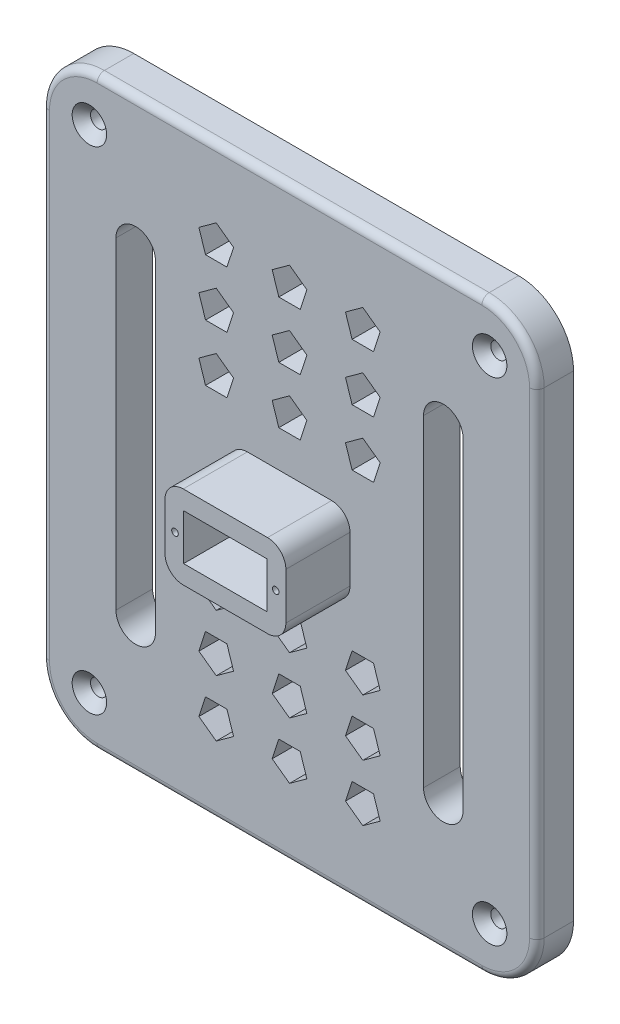
SolidWorks part; units mm, degrees
ref_plane "Front Plane" through (0, 0, 0) normal (1, 0, 0) x (0, 1, 0)
ref_plane "Top Plane" through (0, 0, 0) normal (0, 0, 1) x (0, 1, 0)
ref_plane "Right Plane" through (0, 0, 0) normal (0, 1, 0) x (-1, 0, 0)
sketch "Sketch1" plane through (0, 0, 0) normal (0, 0, 1) x (0, 1, 0)
  line L1 (-60, 62.5) -> (60, 62.5)
  line L2 (-75, 47.5) -> (-75, -47.5)
  line L3 (-60, -62.5) -> (60, -62.5)
  line L4 (75, 47.5) -> (75, -47.5)
  line L5 (-75, 62.5) -> (75, -62.5) construction
  line L6 (-75, -62.5) -> (75, 62.5) construction
  arc A0 (-75, -47.5) -> (-60, -62.5) centre (-60, -47.5) ccw
  arc A1 (60, -62.5) -> (75, -47.5) centre (60, -47.5) ccw
  arc A2 (60, 62.5) -> (75, 47.5) centre (60, 47.5) cw
  arc A3 (-60, 62.5) -> (-75, 47.5) centre (-60, 47.5) ccw
  point P0 (0, 0)
  dimension "D3" = 15
  dimension "D1" = 150
  dimension "D2" = 125
extrude "Boss-Extrude1" add sketch "Sketch1" along normal blind 10
hole_wizard "CSK for M4 Countersunk Flat Head Screw1" positions "Sketch2" profile "Sketch3" countersink size "M4" standard "ISO"
sketch "Sketch2" plane through (0, 0, 10) normal (0, 0, 1) x (0, -1, 0)
  line L0 (-75, 47.5) -> (-75, -47.5) construction
  line L1 (0, 0) -> (0, 48.1391) construction
  line L3 (0, 0) -> (-58.4217, 0) construction
  line L4 (60, 62.5) -> (-60, 62.5) construction
  point P0 (-67.11, 54.61)
  point P15 (67.11, 54.61)
  point P17 (67.11, -54.61)
  point P18 (-67.11, -54.61)
  dimension "D1" = 7.89
  dimension "D2" = 7.89
sketch "Sketch3" plane through (54.61, 67.11, 10) normal (1, 0, 0) x (0, -1, 0)
  line L0 (0, 0) -> (0, 11.3219)
  line L1 (0, 11.3219) -> (2.2, 10)
  line L2 (2.2, 10) -> (2.2, 2.5)
  line L3 (2.2, 2.5) -> (4.7, 0)
  line L5 (4.7, 0) -> (0, 0)
  line L6 (-2.2, 2.5) -> (-4.7, 0) construction
  line L10 (0, 11.3219) -> (-2.2, 10) construction
  line L11 (0, -6.35) -> (0, 107.95) construction
  dimension "Hole Dia." = 4.4
  dimension "Hole Depth" = 10
  dimension "Near C'Sink Dia." = 9.4
  dimension "Near C'Sink Angle" = 90
  dimension "Drill Angle" = 118
sketch "Sketch4" plane through (0, 0, 10) normal (0, 0, 1) x (1, 0, 0)
  line L1 (-11.4, 6.25) -> (11.4, 6.25)
  line L2 (-11.4, 6.25) -> (-11.4, -6.25)
  line L3 (-11.4, -6.25) -> (11.4, -6.25)
  line L4 (11.4, 6.25) -> (11.4, -6.25)
  line L5 (-11.4, 6.25) -> (11.4, -6.25) construction
  line L6 (-11.4, -6.25) -> (11.4, 6.25) construction
  point P0 (0, 0)
  dimension "D1" = 22.8
  dimension "D2" = 12.5
extrude "Extrude-Thin1" add sketch "Sketch4" along normal blind 17.5 thin thin type one direction wall 5.1
fillet "Fillet1" radius 5 4 edges at (16.5, -11.35, 18.75) (16.5, 11.35, 18.75) (-16.5, 11.35, 18.75) (-16.5, -11.35, 18.75)
sketch "Sketch5" plane through (0, 0, 27.5) normal (0, 0, 1) x (1, 0, 0)
  line L0 (0, 0) -> (0, 14.7262) construction
  point P3 (13.75, 0)
  point P4 (-13.75, 0)
  dimension "D1" = 13.75
hole_wizard "Ø1.5mm Dowel Hole1" positions "Sketch6" profile "Sketch7" hole size "Ø1.5" standard "ISO"
sketch "Sketch6" plane through (0, 0, 27.5) normal (0, 0, 1) x (0, -1, 0)
  point P0 (0, -13.75)
  point P3 (0, 13.75)
  point P6 (0, -13.75)
  point P8 (0, 13.75)
sketch "Sketch7" plane through (-13.75, 0, 27.5) normal (1, 0, 0) x (0, -1, 0)
  line L0 (0, 0) -> (0, 10.5408)
  line L1 (0, 10.5408) -> (0.9, 10)
  line L2 (0.9, 10) -> (0.9, 0)
  line L5 (0.9, 0) -> (0, 0)
  line L10 (0, 10.5408) -> (-0.9, 10) construction
  line L11 (0, -6.35) -> (0, 107.95) construction
  dimension "Hole Dia." = 1.8
  dimension "Hole Depth" = 10
  dimension "Drill Angle" = 118
sketch "Sketch8" plane through (0, 0, 10) normal (0, 0, 1) x (1, 0, 0)
  line L0 (0, 0) -> (0, 56.2571) construction
  line L2 (-47.3703, 43.9725) -> (-47.3703, -43.9725)
  line L4 (-36.5771, 43.9725) -> (-36.5771, -43.9725)
  line L5 (-47.3703, 43.9725) -> (-36.5771, -43.9725) construction
  line L6 (-47.3703, -43.9725) -> (-36.5771, 43.9725) construction
  line L7 (36.5771, 43.9725) -> (36.5771, -43.9725)
  line L8 (47.3703, 43.9725) -> (47.3703, -43.9725)
  line L9 (0, 0) -> (0, -69.6004) construction
  line L14 (20, 61.2322) -> (15.2684, 57.7945)
  line L15 (0, 61.2322) -> (-4.7316, 57.7945)
  line L20 (0, 0) -> (35.3698, 0) construction
  line L27 (-11.4, -6.25) -> (11.4, -6.25) construction
  line L28 (-11.4, 6.25) -> (-8.4, 6.25)
  line L29 (-11.4, 6.25) -> (-11.4, -6.25)
  line L30 (-11.4, -6.25) -> (-8.4, -6.25)
  line L31 (-8.4, 6.25) -> (-8.4, -6.25)
  line L32 (-4.7316, 57.7945) -> (-2.9243, 52.2322)
  line L33 (-2.9243, 52.2322) -> (2.9243, 52.2322)
  line L34 (2.9243, 52.2322) -> (4.7316, 57.7945)
  line L35 (4.7316, 57.7945) -> (0, 61.2322)
  line L36 (15.2684, 57.7945) -> (17.0757, 52.2322)
  line L37 (17.0757, 52.2322) -> (22.9243, 52.2322)
  line L38 (22.9243, 52.2322) -> (24.7316, 57.7945)
  line L39 (24.7316, 57.7945) -> (20, 61.2322)
  line L40 (20, 45.7911) -> (15.2684, 42.3534)
  line L41 (15.2684, 42.3534) -> (17.0757, 36.7911)
  line L42 (17.0757, 36.7911) -> (22.9243, 36.7911)
  line L43 (22.9243, 36.7911) -> (24.7316, 42.3534)
  line L44 (24.7316, 42.3534) -> (20, 45.7911)
  line L45 (20, 30.35) -> (15.2684, 26.9123)
  line L46 (15.2684, 26.9123) -> (17.0757, 21.35)
  line L47 (17.0757, 21.35) -> (22.9243, 21.35)
  line L48 (22.9243, 21.35) -> (24.7316, 26.9123)
  line L49 (24.7316, 26.9123) -> (20, 30.35)
  line L50 (0, 45.7911) -> (-4.7316, 42.3534)
  line L51 (-4.7316, 42.3534) -> (-2.9243, 36.7911)
  line L52 (-2.9243, 36.7911) -> (2.9243, 36.7911)
  line L53 (2.9243, 36.7911) -> (4.7316, 42.3534)
  line L54 (4.7316, 42.3534) -> (0, 45.7911)
  line L55 (0, 30.35) -> (-4.7316, 26.9123)
  line L56 (-4.7316, 26.9123) -> (-2.9243, 21.35)
  line L57 (-2.9243, 21.35) -> (2.9243, 21.35)
  line L58 (2.9243, 21.35) -> (4.7316, 26.9123)
  line L59 (4.7316, 26.9123) -> (0, 30.35)
  line L60 (-24.7316, 26.9123) -> (-20, 30.35)
  line L61 (-22.9243, 21.35) -> (-24.7316, 26.9123)
  line L62 (-17.0757, 21.35) -> (-22.9243, 21.35)
  line L63 (-15.2684, 26.9123) -> (-17.0757, 21.35)
  line L64 (-20, 30.35) -> (-15.2684, 26.9123)
  line L65 (-24.7316, 42.3534) -> (-20, 45.7911)
  line L66 (-22.9243, 36.7911) -> (-24.7316, 42.3534)
  line L67 (-17.0757, 36.7911) -> (-22.9243, 36.7911)
  line L68 (-15.2684, 42.3534) -> (-17.0757, 36.7911)
  line L69 (-20, 45.7911) -> (-15.2684, 42.3534)
  line L70 (-24.7316, 57.7945) -> (-20, 61.2322)
  line L71 (-22.9243, 52.2322) -> (-24.7316, 57.7945)
  line L72 (-17.0757, 52.2322) -> (-22.9243, 52.2322)
  line L73 (-15.2684, 57.7945) -> (-17.0757, 52.2322)
  line L74 (-20, 61.2322) -> (-15.2684, 57.7945)
  line L75 (24.7316, -26.9123) -> (20, -30.35)
  line L76 (22.9243, -21.35) -> (24.7316, -26.9123)
  line L77 (17.0757, -21.35) -> (22.9243, -21.35)
  line L78 (15.2684, -26.9123) -> (17.0757, -21.35)
  line L79 (20, -30.35) -> (15.2684, -26.9123)
  line L80 (4.7316, -26.9123) -> (0, -30.35)
  line L81 (2.9243, -21.35) -> (4.7316, -26.9123)
  line L82 (-2.9243, -21.35) -> (2.9243, -21.35)
  line L83 (-4.7316, -26.9123) -> (-2.9243, -21.35)
  line L84 (0, -30.35) -> (-4.7316, -26.9123)
  line L85 (-22.9243, -21.35) -> (-24.7316, -26.9123)
  line L86 (-17.0757, -21.35) -> (-22.9243, -21.35)
  line L87 (-15.2684, -26.9123) -> (-17.0757, -21.35)
  line L88 (-20, -30.35) -> (-15.2684, -26.9123)
  line L89 (-24.7316, -26.9123) -> (-20, -30.35)
  line L90 (-22.9243, -36.7911) -> (-24.7316, -42.3534)
  line L91 (-17.0757, -36.7911) -> (-22.9243, -36.7911)
  line L92 (-15.2684, -42.3534) -> (-17.0757, -36.7911)
  line L93 (-20, -45.7911) -> (-15.2684, -42.3534)
  line L94 (-24.7316, -42.3534) -> (-20, -45.7911)
  line L95 (4.7316, -42.3534) -> (0, -45.7911)
  line L96 (2.9243, -36.7911) -> (4.7316, -42.3534)
  line L97 (-2.9243, -36.7911) -> (2.9243, -36.7911)
  line L98 (-4.7316, -42.3534) -> (-2.9243, -36.7911)
  line L99 (0, -45.7911) -> (-4.7316, -42.3534)
  line L100 (24.7316, -42.3534) -> (20, -45.7911)
  line L101 (22.9243, -36.7911) -> (24.7316, -42.3534)
  line L102 (17.0757, -36.7911) -> (22.9243, -36.7911)
  line L103 (15.2684, -42.3534) -> (17.0757, -36.7911)
  line L104 (20, -45.7911) -> (15.2684, -42.3534)
  line L105 (24.7316, -57.7945) -> (20, -61.2322)
  line L106 (22.9243, -52.2322) -> (24.7316, -57.7945)
  line L107 (17.0757, -52.2322) -> (22.9243, -52.2322)
  line L108 (15.2684, -57.7945) -> (17.0757, -52.2322)
  line L109 (20, -61.2322) -> (15.2684, -57.7945)
  line L110 (4.7316, -57.7945) -> (0, -61.2322)
  line L111 (2.9243, -52.2322) -> (4.7316, -57.7945)
  line L112 (-2.9243, -52.2322) -> (2.9243, -52.2322)
  line L113 (-4.7316, -57.7945) -> (-2.9243, -52.2322)
  line L114 (0, -61.2322) -> (-4.7316, -57.7945)
  line L115 (-22.9243, -52.2322) -> (-24.7316, -57.7945)
  line L116 (-17.0757, -52.2322) -> (-22.9243, -52.2322)
  line L117 (-15.2684, -57.7945) -> (-17.0757, -52.2322)
  line L118 (-20, -61.2322) -> (-15.2684, -57.7945)
  line L119 (-24.7316, -57.7945) -> (-20, -61.2322)
  line L120 (11.5, 11.35) -> (-11.5, 11.35) construction
  arc A0 (-36.5771, 43.9725) -> (-47.3703, 43.9725) centre (-41.9737, 43.9725) ccw
  arc A1 (-47.3703, -43.9725) -> (-36.5771, -43.9725) centre (-41.9737, -43.9725) ccw
  arc A2 (47.3703, -43.9725) -> (36.5771, -43.9725) centre (41.9737, -43.9725) cw
  arc A3 (36.5771, 43.9725) -> (47.3703, 43.9725) centre (41.9737, 43.9725) cw
  circle A16 centre (0, 56.2571) radius 4.0249 construction
  point P0 (-41.9737, 0)
  point P24 (0, -23.7942)
  dimension "D2" = 3
  dimension "D1" = 9
  dimension "D5" = 10
  dimension "D3" = 2
  dimension "D4" = 3
extrude "Cut-Extrude1" cut sketch "Sketch8" against normal through all
sketch "Sketch9" plane through (0, 0, 0) normal (0, 0, -1) x (1, 0, 0)
  line L0 (-47.5, 75) -> (47.5, 75) construction
  line L1 (-52.5, 80) -> (52.5, 80)
  line L2 (-67.5, 65) -> (-67.5, -65)
  line L3 (-52.5, -80) -> (52.5, -80)
  line L4 (67.5, 65) -> (67.5, -65)
  line L5 (-67.5, 80) -> (67.5, -80) construction
  line L6 (-67.5, -80) -> (67.5, 80) construction
  line L7 (62.5, 60) -> (62.5, -60) construction
  line L9 (-47.5, 75) -> (47.5, 75)
  line L10 (-62.5, 60) -> (-62.5, -60)
  line L11 (-47.5, -75) -> (47.5, -75)
  line L12 (62.5, 60) -> (62.5, -60)
  line L13 (-62.5, 75) -> (62.5, -75) construction
  line L14 (-62.5, -75) -> (62.5, 75) construction
  arc A0 (-62.5, -60) -> (-47.5, -75) centre (-47.5, -60) ccw
  arc A1 (47.5, -75) -> (62.5, -60) centre (47.5, -60) ccw
  arc A2 (47.5, 75) -> (62.5, 60) centre (47.5, 60) cw
  arc A3 (-47.5, 75) -> (-62.5, 60) centre (-47.5, 60) ccw
  arc A4 (52.5, -80) -> (67.5, -65) centre (52.5, -65) ccw
  arc A5 (-67.5, -65) -> (-52.5, -80) centre (-52.5, -65) ccw
  arc A6 (-52.5, 80) -> (-67.5, 65) centre (-52.5, 65) ccw
  arc A7 (52.5, 80) -> (67.5, 65) centre (52.5, 65) cw
  point P0 (0, 0)
  point P10 (0, 0)
  dimension "D5" = 15
  dimension "D6" = 15
  dimension "D1" = 5
  dimension "D2" = 5
  dimension "D3" = 125
  dimension "D4" = 150
extrude "Boss-Extrude3" add sketch "Sketch9" against normal blind 10
fillet "Fillet2" radius 2 8 edges at (0, 80, 10) (-63.1066, 75.6066, 10) (-67.5, 0, 10) (-63.1066, -75.6066, 10) (0, -80, 10) (63.1066, -75.6066, 10) (67.5, 0, 10) (63.1066, 75.6066, 10)
